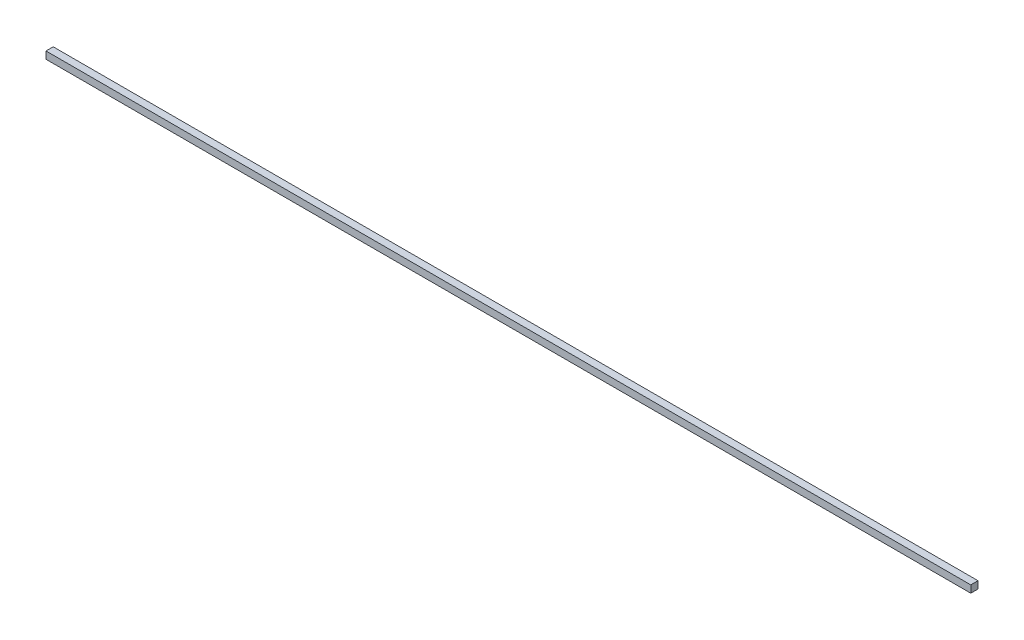
SolidWorks part; units mm, degrees
material "Hexcel AS4C (3000 Filaments)"
ref_plane "Front Plane" through (0, 0, 0) normal (0, 0, 1) x (1, 0, 0)
ref_plane "Top Plane" through (0, 0, 0) normal (0, 1, 0) x (1, 0, 0)
ref_plane "Right Plane" through (0, 0, 0) normal (1, 0, 0) x (0, 0, -1)
sketch "Sketch1" plane through (0, 0, 0) normal (1, 0, 0) x (0, 0, -1)
  line L1 (0, 0) -> (6.35, 0)
  line L2 (0, 0) -> (0, 6.35)
  line L3 (0, 6.35) -> (6.35, 6.35)
  line L4 (6.35, 0) -> (6.35, 6.35)
  dimension "D1" = 6.35
  dimension "D2" = 6.35
extrude "Boss-Extrude1" add sketch "Sketch1" along normal blind 812.8 contours L3 L4 L1 L2
